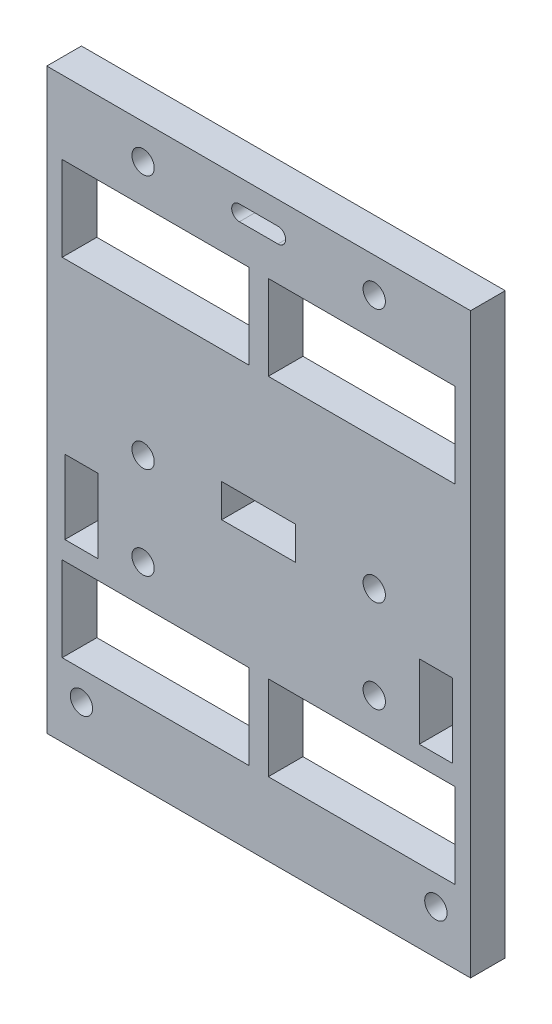
SolidWorks part; units mm, degrees
ref_plane "Front Plane" through (0, 0, 0) normal (0, 0, 1) x (1, 0, 0)
ref_plane "Top Plane" through (0, 0, 0) normal (0, 1, 0) x (1, 0, 0)
ref_plane "Right Plane" through (0, 0, 0) normal (1, 0, 0) x (0, 0, -1)
sketch "Sketch1" plane through (0, 0, 0) normal (0, 0, 1) x (1, 0, 0)
  line L0 (0, -37.5) -> (0, 37.5) construction
  line L1 (-27.5, -37.5) -> (27.5, -37.5)
  line L2 (-27.5, -37.5) -> (-27.5, 37.5)
  line L3 (-27.5, 37.5) -> (27.5, 37.5)
  line L4 (27.5, -37.5) -> (27.5, 37.5)
  line L5 (-27.5, -37.5) -> (27.5, 37.5) construction
  line L6 (-27.5, 37.5) -> (27.5, -37.5) construction
  line L7 (-27.5, 0) -> (27.5, 0) construction
  line L8 (-27.5, 22.5) -> (27.5, 22.5) construction
  line L9 (25.5, 17) -> (1.25, 28) construction
  line L10 (-25.5, 28) -> (-1.25, 28)
  line L11 (-25.5, 28) -> (-25.5, 17)
  line L12 (-25.5, 17) -> (-1.25, 17)
  line L13 (-1.25, 28) -> (-1.25, 17)
  line L14 (-25.5, 28) -> (-1.25, 17) construction
  line L15 (-25.5, 17) -> (-1.25, 28) construction
  line L16 (25.5, 28) -> (1.25, 17) construction
  line L17 (1.25, 28) -> (1.25, 17)
  line L18 (25.5, 17) -> (1.25, 17)
  line L19 (25.5, 28) -> (25.5, 17)
  line L20 (25.5, 28) -> (1.25, 28)
  line L21 (25.5, -28) -> (1.25, -17) construction
  line L22 (-25.5, -17) -> (-1.25, -28) construction
  line L23 (-25.5, -28) -> (-1.25, -17) construction
  line L24 (25.5, -17) -> (1.25, -28) construction
  line L25 (25.5, -28) -> (1.25, -28)
  line L26 (25.5, -28) -> (25.5, -17)
  line L27 (25.5, -17) -> (1.25, -17)
  line L28 (1.25, -28) -> (1.25, -17)
  line L29 (-1.25, -28) -> (-1.25, -17)
  line L30 (-25.5, -17) -> (-1.25, -17)
  line L31 (-25.5, -28) -> (-25.5, -17)
  line L32 (-25.5, -28) -> (-1.25, -28)
  point P0 (0, 0)
  point P12 (-13.375, 22.5)
  point P21 (13.375, 22.5)
  point P30 (13.375, -22.5)
  point P31 (-13.375, -22.5)
  dimension "D1" = 55
  dimension "D2" = 75
  dimension "D3" = 22.5
  dimension "D4" = 24.25
  dimension "D5" = 11
  dimension "D6" = 1.25
extrude "Boss-Extrude1" add sketch "Sketch1" along normal blind 4.5
sketch "Sketch2" plane through (0, 0, 4.5) normal (0, 0, 1) x (1, 0, 0)
  line L0 (0, -37.5) -> (0, 37.5) construction
  line L1 (-27.5, -37.5) -> (27.5, -37.5) construction
  line L2 (27.5, 37.5) -> (-27.5, 37.5) construction
  line L3 (-27.5, 0) -> (27.5, 0) construction
  line L4 (-27.5, 37.5) -> (-27.5, -37.5) construction
  line L5 (27.5, -37.5) -> (27.5, 37.5) construction
  line L6 (-15, 0) -> (15, 0) construction
  circle A0 centre (-15, 33) radius 1.45
  circle A1 centre (15, 33) radius 1.45
  circle A2 centre (15, 0) radius 1.45
  circle A3 centre (-15, 0) radius 1.45
  dimension "D1" = 2.9
  dimension "D7" = 2.9
  dimension "D8" = 2.9
  dimension "D2" = 15
  dimension "D3" = 33
  dimension "D4" = 30
  dimension "D5" = 15
  dimension "D6" = 0
extrude "screwHoles" cut sketch "Sketch2" against normal through all
sketch "Sketch3" plane through (0, 0, 4.5) normal (0, 0, 1) x (1, 0, 0)
  line L0 (-27.5, 9) -> (26.0486, 9) construction
  line L1 (-27.5, 37.5) -> (-27.5, -37.5) construction
  line L3 (0, 37.5) -> (0, -37.5) construction
  line L4 (27.5, 37.5) -> (-27.5, 37.5) construction
  line L5 (-27.5, -37.5) -> (27.5, -37.5) construction
  line L6 (18.95, 6.8) -> (9.05, 11.2) construction
  line L7 (-18.95, 11.2) -> (-9.05, 11.2)
  line L8 (-18.95, 11.2) -> (-18.95, 6.8)
  line L9 (-18.95, 6.8) -> (-9.05, 6.8)
  line L10 (-9.05, 11.2) -> (-9.05, 6.8)
  line L11 (-18.95, 11.2) -> (-9.05, 6.8) construction
  line L12 (-18.95, 6.8) -> (-9.05, 11.2) construction
  line L13 (18.95, 11.2) -> (9.05, 6.8) construction
  line L14 (9.05, 11.2) -> (9.05, 6.8)
  line L15 (18.95, 6.8) -> (9.05, 6.8)
  line L16 (18.95, 11.2) -> (18.95, 6.8)
  line L17 (18.95, 11.2) -> (9.05, 11.2)
  line L18 (-27.5, 37.5) -> (-27.5, -37.5) construction
  point P2 (-27.5, 0)
  point P12 (-14, 9)
  point P21 (14, 9)
  dimension "D1" = 9.9
  dimension "D2" = 4.4
  dimension "D3" = 14
  dimension "D4" = 9
extrude "BeltClamp" [suppressed] cut sketch "Sketch3" against normal through all
sketch "Sketch4" plane through (0, 0, 4.5) normal (0, 0, 1) x (1, 0, 0)
  line L0 (-27.5, 0) -> (27.5, 0) construction
  line L1 (-27.5, 37.5) -> (-27.5, -37.5) construction
  line L2 (27.5, -37.5) -> (27.5, 37.5) construction
  line L4 (-4.8, 2.15) -> (4.8, 2.15)
  line L5 (-4.8, 2.15) -> (-4.8, -2.15)
  line L6 (-4.8, -2.15) -> (4.8, -2.15)
  line L7 (4.8, 2.15) -> (4.8, -2.15)
  line L8 (-4.8, 2.15) -> (4.8, -2.15) construction
  line L9 (-4.8, -2.15) -> (4.8, 2.15) construction
  circle A0 centre (-15, 0) radius 1.45 construction
  point P6 (0, 0)
  dimension "D1" = 9.6
  dimension "D2" = 4.3
  dimension "D3" = 0
extrude "mountingPlateTab" cut sketch "Sketch4" against normal through all
sketch "Sketch5" plane through (0, 0, 4.5) normal (0, 0, 1) x (1, 0, 0)
  line L0 (-27.5, -9.75) -> (27.5, -9.75) construction
  line L1 (-27.5, 37.5) -> (-27.5, -37.5) construction
  line L2 (27.5, -37.5) -> (27.5, 37.5) construction
  line L4 (0, -37.5) -> (0, 37.5) construction
  line L5 (-27.5, -37.5) -> (27.5, -37.5) construction
  line L6 (27.5, 37.5) -> (-27.5, 37.5) construction
  line L7 (-20.85, -14.55) -> (-25.15, -4.95) construction
  line L8 (20.85, -4.95) -> (25.15, -4.95)
  line L9 (20.85, -4.95) -> (20.85, -14.55)
  line L10 (20.85, -14.55) -> (25.15, -14.55)
  line L11 (25.15, -4.95) -> (25.15, -14.55)
  line L12 (20.85, -4.95) -> (25.15, -14.55) construction
  line L13 (20.85, -14.55) -> (25.15, -4.95) construction
  line L14 (-20.85, -4.95) -> (-25.15, -14.55) construction
  line L15 (-25.15, -4.95) -> (-25.15, -14.55)
  line L16 (-20.85, -14.55) -> (-25.15, -14.55)
  line L17 (-20.85, -4.95) -> (-20.85, -14.55)
  line L18 (-20.85, -4.95) -> (-25.15, -4.95)
  line L19 (23, -9.75) -> (23, -37.5) construction
  line L20 (-23, -9.75) -> (-23, -37.5) construction
  circle A0 centre (23, -31.75) radius 1.45
  circle A1 centre (-23, -31.75) radius 1.45
  point P15 (23, -9.75)
  point P24 (-23, -9.75)
  dimension "D5" = 2.9
  dimension "D2" = 9.6
  dimension "D3" = 4.3
  dimension "D4" = 23
  dimension "D6" = 22
  dimension "D1" = 9.75
extrude "BraceTabs" cut sketch "Sketch5" against normal through all
sketch "Sketch6" plane through (0, 0, 4.5) normal (0, 0, 1) x (1, 0, 0)
  line L0 (-25.15, -9.75) -> (25.15, -9.75) construction
  line L1 (-25.15, -4.95) -> (-25.15, -14.55) construction
  line L2 (25.15, -14.55) -> (25.15, -4.95) construction
  line L3 (0, -2.15) -> (0, -37.5) construction
  line L4 (-4.8, -2.15) -> (4.8, -2.15) construction
  line L5 (-27.5, -37.5) -> (27.5, -37.5) construction
  line L6 (23, -14.55) -> (23, -4.95) construction
  line L7 (20.85, -14.55) -> (25.15, -14.55) construction
  line L8 (25.15, -4.95) -> (20.85, -4.95) construction
  line L9 (20.85, -4.95) -> (20.85, -14.55) construction
  line L10 (19.85, -15.55) -> (26.15, -15.55)
  line L11 (19.85, -15.55) -> (19.85, -3.95)
  line L12 (19.85, -3.95) -> (26.15, -3.95)
  line L13 (26.15, -15.55) -> (26.15, -3.95)
  line L14 (19.85, -15.55) -> (26.15, -3.95) construction
  line L15 (19.85, -3.95) -> (26.15, -15.55) construction
  line L16 (-19.85, -3.95) -> (-26.15, -15.55) construction
  line L17 (-19.85, -15.55) -> (-26.15, -3.95) construction
  line L18 (-23, -14.55) -> (-23, -4.95) construction
  line L19 (-26.15, -15.55) -> (-26.15, -3.95)
  line L20 (-19.85, -3.95) -> (-26.15, -3.95)
  line L21 (-19.85, -15.55) -> (-19.85, -3.95)
  line L22 (-19.85, -15.55) -> (-26.15, -15.55)
  circle A0 centre (23, -9.75) radius 1.45
  circle A1 centre (-23, -9.75) radius 1.45
  point P18 (23, -9.75)
  dimension "D3" = 2.9
  dimension "D1" = 1
  dimension "D2" = 1
extrude "FrontToRear1" [suppressed] add sketch "Sketch6" against normal up to surface (4.5 mm away)
sketch "Sketch7" plane through (0, 0, 4.5) normal (0, 0, 1) x (1, 0, 0)
  line L0 (4.8, 2.15) -> (-4.8, 2.15) construction
  line L1 (-20, -3.15) -> (20, -3.15)
  line L2 (-20, -3.15) -> (-20, 3.15)
  line L3 (-20, 3.15) -> (20, 3.15)
  line L4 (20, -3.15) -> (20, 3.15)
  line L5 (-20, -3.15) -> (20, 3.15) construction
  line L6 (-20, 3.15) -> (20, -3.15) construction
  circle A0 centre (15, 0) radius 1.45 construction
  point P0 (0, 0)
  dimension "D1" = 1
  dimension "D2" = 5
extrude "FrontToRear2" [suppressed] add sketch "Sketch7" against normal through all
sketch "Sketch8" plane through (0, 0, 4.5) normal (0, 0, 1) x (1, 0, 0)
  line L0 (-27.5, -12) -> (27.5, -12) construction
  line L1 (-27.5, 37.5) -> (-27.5, -37.5) construction
  line L2 (27.5, -37.5) -> (27.5, 37.5) construction
  line L3 (0, -37.5) -> (0, 0) construction
  line L4 (-27.5, -37.5) -> (27.5, -37.5) construction
  circle A0 centre (-15, -12) radius 1.45
  circle A1 centre (15, -12) radius 1.45
  dimension "D2" = 2.9
  dimension "D1" = 12
  dimension "D3" = 15
extrude "ExpansionScrewholes" cut sketch "Sketch8" against normal through all
sketch "Sketch12" plane through (0, 0, 4.5) normal (0, 0, 1) x (1, 0, 0)
  line L0 (0, 37.5) -> (0, 0) construction
  line L1 (27.5, 37.5) -> (-27.5, 37.5) construction
  line L2 (-2.5, 33.5) -> (2.5, 33.5) construction
  line L3 (-2.5, 34.5) -> (2.5, 34.5)
  line L4 (-2.5, 32.5) -> (2.5, 32.5)
  arc A0 (-2.5, 34.5) -> (-2.5, 32.5) centre (-2.5, 33.5) ccw
  arc A1 (2.5, 32.5) -> (2.5, 34.5) centre (2.5, 33.5) ccw
  point P7 (0, 33.5)
  dimension "D1" = 3
  dimension "D2" = 2
  dimension "D3" = 5
extrude "CableTieSlot" cut sketch "Sketch12" against normal through all
sketch "Sketch11" [suppressed] plane through (0, 0, 4.5) normal (0, 0, 1) x (1, 0, 0)
  line L0 (13.5615, -8.85) -> (27.5, -8.85) construction
  line L1 (27.5, -37.5) -> (27.5, 37.5) construction
  line L2 (0, 37.5) -> (0, -37.5) construction
  line L3 (36.5, -14.85) -> (18.5, -14.85)
  line L4 (36.5, -14.85) -> (36.5, -2.85)
  line L5 (36.5, -2.85) -> (18.5, -2.85)
  line L6 (18.5, -14.85) -> (18.5, -2.85)
  line L7 (36.5, -14.85) -> (18.5, -2.85) construction
  line L8 (36.5, -2.85) -> (18.5, -14.85) construction
  line L11 (-36.5, -2.85) -> (-18.5, -14.85) construction
  line L12 (-36.5, -14.85) -> (-18.5, -2.85) construction
  line L13 (-18.5, -14.85) -> (-18.5, -2.85)
  line L14 (-36.5, -2.85) -> (-18.5, -2.85)
  line L15 (-36.5, -14.85) -> (-36.5, -2.85)
  line L16 (-36.5, -14.85) -> (-18.5, -14.85)
  line L17 (36.5, -2.85) -> (18.5, -14.85) construction
  line L18 (20.65, -14.85) -> (25.35, -14.85) construction
  line L19 (27.5, 37.5) -> (-27.5, 37.5) construction
  line L20 (-27.5, -37.5) -> (27.5, -37.5) construction
  dimension "D1" = 9
  dimension "D2" = 12
  dimension "D3" = 0
extrude "Cut-Extrude2" [suppressed] cut sketch "Sketch11" against normal through all
sketch "Sketch10" plane through (0, 0, 4.5) normal (0, 0, 1) x (1, 0, 0)
  line L0 (4.7446, 1) -> (27.5, 1) construction
  line L1 (-4.8, 0) -> (4.8, 0) construction
  line L2 (27.5, -37.5) -> (27.5, 37.5) construction
  line L3 (0, 2.15) -> (0, -2.15) construction
  line L4 (36.5, 4) -> (18.5, 4)
  line L5 (36.5, 4) -> (36.5, -2)
  line L6 (36.5, -2) -> (18.5, -2)
  line L7 (18.5, 4) -> (18.5, -2)
  line L8 (36.5, 4) -> (18.5, -2) construction
  line L9 (36.5, -2) -> (18.5, 4) construction
  line L10 (4.8, 2.15) -> (-4.8, 2.15) construction
  line L11 (-4.8, -2.15) -> (4.8, -2.15) construction
  line L12 (-36.5, -2) -> (-18.5, 4) construction
  line L13 (-36.5, 4) -> (-18.5, -2) construction
  line L14 (-4.7446, 1) -> (-27.5, 1) construction
  line L15 (-18.5, 4) -> (-18.5, -2)
  line L16 (-36.5, -2) -> (-18.5, -2)
  line L17 (-36.5, 4) -> (-36.5, -2)
  line L18 (-36.5, 4) -> (-18.5, 4)
  line L19 (36.5, -2) -> (18.5, 4) construction
  line L20 (-4.8, 2.15) -> (-4.8, -2.15) construction
  line L21 (4.8, -2.15) -> (4.8, 2.15) construction
  dimension "D1" = 6
  dimension "D2" = 9
  dimension "D3" = 1
extrude "CableTieSlots" [suppressed] cut sketch "Sketch10" against normal through all
sketch "Sketch9" [suppressed] plane through (0, 0, 4.5) normal (0, 0, 1) x (1, 0, 0)
  line L0 (-27.5, -37.5) -> (27.5, -37.5) construction
  line L5 (-9, -42.5) -> (9, -42.5)
  line L6 (-9, -42.5) -> (-9, -34.5)
  line L7 (-7, -32.5) -> (7, -32.5)
  line L8 (9, -42.5) -> (9, -34.5)
  line L9 (-9, -42.5) -> (9, -32.5) construction
  line L10 (-9, -32.5) -> (9, -42.5) construction
  arc A0 (7, -32.5) -> (9, -34.5) centre (7, -34.5) cw
  arc A1 (-9, -34.5) -> (-7, -32.5) centre (-7, -34.5) cw
  point P9 (0, -37.5)
  dimension "D3" = 2
  dimension "D1" = 18
  dimension "D2" = 5
extrude "RearFanSlot" [suppressed] cut sketch "Sketch9" against normal through all
sketch "Sketch13" [suppressed] plane through (0, 0, 4.5) normal (0, 0, 1) x (1, 0, 0)
  line L1 (-7, -2.85) -> (7, -2.85)
  line L2 (-7, -2.85) -> (-7, -11.85)
  line L3 (-7, -11.85) -> (7, -11.85)
  line L4 (7, -2.85) -> (7, -11.85)
  line L5 (-7, -2.85) -> (7, -11.85) construction
  line L6 (-7, -11.85) -> (7, -2.85) construction
  line L9 (0, 37.5) -> (0, -7.35) construction
  line L10 (-18.5, -2.85) -> (-27.5, -2.85) construction
  line L11 (27.5, 37.5) -> (-27.5, 37.5) construction
  line L13 (-27.5, -14.85) -> (-18.5, -14.85) construction
  point P0 (0, -7.35)
  dimension "D1" = 3
  dimension "D2" = 0
  dimension "D3" = 7
extrude "Cut-Extrude3" [suppressed] cut sketch "Sketch13" against normal through all
sketch "Sketch14" [suppressed] plane through (0, 0, 4.5) normal (0, 0, 1) x (1, 0, 0)
  line L0 (25.2, -4.85) -> (20.8, -4.85) construction
  line L1 (25.2, -4.85) -> (20.8, -4.85)
  line L2 (25.2, -4.85) -> (25.2, -14.65)
  line L3 (25.2, -14.65) -> (20.8, -14.65)
  line L4 (20.8, -4.85) -> (20.8, -14.65)
  line L5 (25.2, -14.65) -> (25.2, -4.85) construction
  line L6 (0, 0) -> (0, -6.835) construction
  line L7 (-20.8, -4.85) -> (-20.8, -14.65)
  line L8 (-25.2, -14.65) -> (-20.8, -14.65)
  line L9 (-25.2, -4.85) -> (-25.2, -14.65)
  line L10 (-25.2, -4.85) -> (-20.8, -4.85)
extrude "Boss-Extrude2" [suppressed] add sketch "Sketch14" against normal through all
equation "\"X-ROD-SPACING\"=45"
equation "\"Y-ROD-SPACING\"=75"
equation "\"Z-ROD-SPACING\"=17.5"
equation "\"Y-BED-OFFSET\"=2"
equation "\"Y-BED-ROD-INSET\"=3.5"
equation "\"Y-BED-SCREW-SPACING\"=209"
equation "\"Y-BED-SCREW-CUTOUT-SLOT-HEIGHT\"=2"
equation "\"T-SLOT-NUT-FILLET-RADIUS\"=0.5"
equation "\"T-SLOT-SCREW-SHAFT-RADIUS\"=1.55"
equation "\"T-SLOT-SCREW-SHAFT-CUTOUT-LENGTH\"=11"
equation "\"T-SLOT-NUT-DEPTH\"=3.5"
equation "\"T-SLOT-NUT-WIDTH\"=2.85"
equation "\"T-SLOT-NUT-END-DISTANCE\"=8"
equation "\"ACRYLIC-THICKNESS\"=10"
equation "\"ACRYLIC-THICKNESS2\"=4.5"
equation "\"ACRYLIC-TAB-CUTOUT-SIZE\"=\"ACRYLIC-THICKNESS\"+\"ACRYLIC-TAB-TOLERANCE\"*2"
equation "\"ACRYLIC-TAB-WIDTH\"=\"ACRYLIC-THICKNESS\""
equation "\"ACRYLIC-M3-HOLE\"=2.9"
equation "\"SMOOTHROD-CAP-SCREW-DISTANCE\"=20"
equation "\"FRAME-WIDTH-INNER\"=370"
equation "\"NEMA17-HOLE-SPACING\"=31"
equation "\"NEMA17-CENTRAL-CUTOUT\"=22.5"
equation "\"Z-BRACKET-REACH\"=55"
equation "\"Z-ROD-INSET\"=13.5"
equation "\"TOP-BRACKET-SPACING\"=40"
equation "\"SMOOTHROD-X-LENGTH\"=350"
equation "\"SMOOTHROD-Y-LENGTH\"=350"
equation "\"SMOOTHROD-Z-LENGTH\"=350"
equation "\"SMOOTHROD-TIGHTENING-HEADROOM\"=.25"
equation "\"LEADSCREW-Z-LENGTH\"=300"
equation "\"SCREW-LENGTH-FRAME\"=\"ACRYLIC-THICKNESS\" + 10"
equation "\"SCREW-LENGTH-MOTOR\"=\"ACRYLIC-THICKNESS\" + 5"
equation "\"SCREW-HEAD-RADIUS\"=6"
equation "\"PRINTED-X-SMOOTHROD-DIAMETER\"=9.0"
equation "\"PRINTED-X-SMOOTHROD-CUTOUT\"=10"
equation "\"PRINTED-X-BASE-HEIGHT\"=10"
equation "\"PRINTED-LM8UU-CUTOUT-SIZE\"=15.5"
equation "\"PRINTED-LM8UU-CUTOUT-LENGTH\"=24.5"
equation "\"PRINTED-X-IDLER-HEIGHT\"=16"
equation "\"PSU-MOUNTING-WIDTH\"=95"
equation "\"PSU-MOUNTING-HEIGHT\"=177"
equation "\"Y-BELT-TO-ROD-DISTANCE\"=20"
equation "\"SPOOL-HOLDER-ROD-SPACING\"=150"
equation "\"D3@Sketch1\"=\"X-ROD-SPACING\"/2"
equation "\"D4@Sketch1\"=\"ACRYLIC-X-CARRIAGE-LM8UU-CUTOUT-WIDTH\""
equation "\"D1@Boss-Extrude1\"=\"ACRYLIC-THICKNESS2\""
equation "\"D1@Sketch2\"=\"ACRYLIC-M3-HOLE\""
equation "\"D1@Sketch3\"=\"ACRYLIC-TAB-CUTOUT-SIZE\""
equation "\"D2@Sketch3\"=\"ACRYLIC-THICKNESS2\"+\"ACRYLIC-TAB-TOLERANCE\"*2"
equation "\"ACRYLIC-X-CARRIAGE-WIDTH\"=55"
equation "\"ACRYLIC-X-CARRIAGE-HEIGHT\"=75"
equation "\"D1@Sketch1\"=\"ACRYLIC-X-CARRIAGE-WIDTH\""
equation "\"D2@Sketch1\"=\"ACRYLIC-X-CARRIAGE-HEIGHT\""
equation "\"ACRYLIC-X-CARRIAGE-CENTER-TAB-SPACING\"=14"
equation "\"D3@Sketch3\"=\"ACRYLIC-X-CARRIAGE-CENTER-TAB-SPACING\""
equation "\"SCREW-LENGTH-EXTRUDER\"=28"
equation "\"ACRYLIC-X-CARRIAGE-SCREW-SPACING-X\"=15"
equation "\"ACRYLIC-X-CARRIAGE-SCREW-SPACING-Y\"=33"
equation "\"D2@Sketch2\"=\"ACRYLIC-X-CARRIAGE-SCREW-SPACING-X\""
equation "\"D3@Sketch2\"=\"ACRYLIC-X-CARRIAGE-SCREW-SPACING-Y\""
equation "\"D1@Sketch4\"=\"ACRYLIC-TAB-WIDTH\"-\"KERF\"*4"
equation "\"D2@Sketch4\"=\"ACRYLIC-THICKNESS2\"-\"KERF\"*2"
equation "\"D2@Sketch5\"=\"ACRYLIC-TAB-WIDTH\"-\"KERF\"*4"
equation "\"D3@Sketch5\"=\"ACRYLIC-THICKNESS2\"-\"KERF\"*2"
equation "\"ACRYLIC-X-CARRIAGE-EXTRUDER-SHELF-DEPTH\"=\"ACRYLIC-X-CARRIAGE-EXTRUDER-OFFSET\" + 28"
equation "\"ACRYLIC-X-CARRIAGE-EXTRUDER-BRACE-SPACING\"=23"
equation "\"D4@Sketch5\"=\"ACRYLIC-X-CARRIAGE-EXTRUDER-BRACE-SPACING\""
equation "\"D4@Sketch2\"=\"ACRYLIC-X-CARRIAGE-SCREW-SPACING-X\"*2"
equation "\"D5@Sketch2\"=\"ACRYLIC-X-CARRIAGE-SCREW-SPACING-X\""
equation "\"D7@Sketch2\"=\"ACRYLIC-M3-HOLE\""
equation "\"D8@Sketch2\"=\"ACRYLIC-M3-HOLE\""
equation "\"ACRYLIC-X-CARRIAGE-LM8UU-CUTOUT-WIDTH\"=24.25"
equation "\"ACRYLIC-TAB-TOLERANCE\"=-.05"
equation "\"ACRYLIC-X-CARRIAGE-EXTRUDER-OFFSET\"=26"
equation "\"ACRYLIC-X-CARRIAGE-EXTRUDER-ANGLE\"=90"
equation "\"ACRYLIC-X-CARRIAGE-EXTRUDER-BRACE-TAB-OFFSET\"=20"
equation "\"ACRYLIC-X-CARRIAGE-EXTRUDER-BRACE-HEIGHT\"=35"
equation "\"ACRYLIC-X-CARRIAGE-EXTRUDER-BRACE-SCREW-SPACING\"=22"
equation "\"D5@Sketch5\"=\"ACRYLIC-M3-HOLE\""
equation "\"D3@Sketch6\"=\"ACRYLIC-M3-HOLE\""
equation "\"ACRYLIC-X-CARRIAGE-LM8UU-CUTOUT-HEIGHT\"=11.0"
equation "\"ACRYLIC-X-CARRIAGE-DUAL-WIDTH-MULTIPLIER\"=1.65"
equation "\"ACRYLIC-X-CARRIAGE-DUAL-HOTEND-SPACING\"=42"
equation "\"ACRYLIC-X-CARRIAGE-DUAL-WIDTH\"=75"
equation "\"ACRYLIC-X-CARRIAGE-DUAL-HOTEND-SEPARATION\"=36"
equation "\"ACRYLIC-X-CARRIAGE-DUAL-MOUNT-PLATE-DEPTH\"=75"
equation "\"ACRYLIC-X-CARRIAGE-DUAL-MOUNT-BRACE-WIDTH\"=33"
equation "\"ACRYLIC-X-CARRIAGE-DUAL-MOUNT-SCREW-WIDTH\"=40"
equation "\"D5@Sketch1\"=\"ACRYLIC-X-CARRIAGE-LM8UU-CUTOUT-HEIGHT\""
equation "\"D2@Sketch8\"=\"ACRYLIC-M3-HOLE\""
equation "\"D1@Sketch5\"=\"ACRYLIC-THICKNESS2\"/2 + 7.5"
equation "\"KERF\"=0.1"
equation "\"PRINTED-M3-HOLE\"=3.5"
equation "\"PRINTED-M3-NUT-AF\"=6.25"
equation "\"ACRYLIC-X-CARRIAGE-DUAL-FAN-OFFSET\"=52"
equation "\"ACRYLIC-X-CARRIAGE-DUAL-FAN-HEIGHT\"=20"
equation "\"BLOWER-FAN-WIDTH\"=15"
